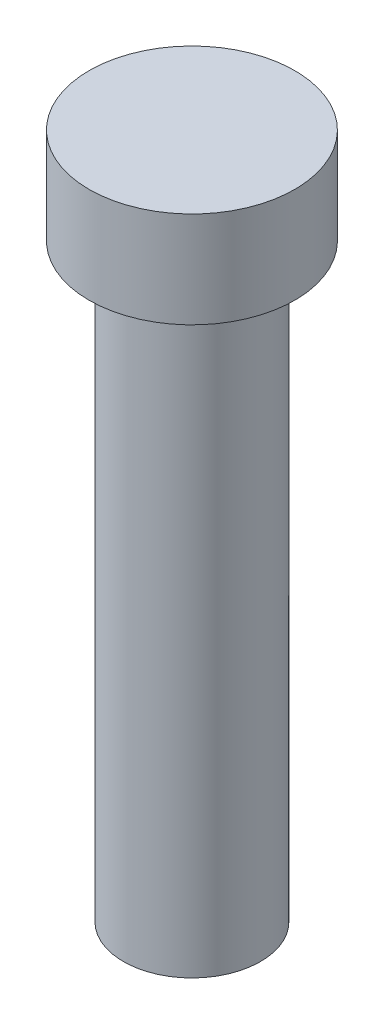
SolidWorks part; units mm, degrees
ref_plane "Front Plane" through (0, 0, 0) normal (1, 0, 0) x (0, 1, 0)
ref_plane "Top Plane" through (0, 0, 0) normal (0, 0, 1) x (0, 1, 0)
ref_plane "Right Plane" through (0, 0, 0) normal (0, 1, 0) x (-1, 0, 0)
sketch "Sketch1" plane through (0, 0, 0) normal (0, 1, 0) x (-1, 0, 0)
  circle A0 centre (0, 0) radius 7.5
  dimension "D1" = 15
extrude "Boss-Extrude1" add sketch "Sketch1" along normal blind 7
sketch "Sketch2" plane through (0, 0, 0) normal (0, -1, 0) x (1, 0, 0)
  circle A0 centre (0, 0) radius 5
  dimension "D1" = 10
extrude "Boss-Extrude2" add sketch "Sketch2" along normal blind 43
